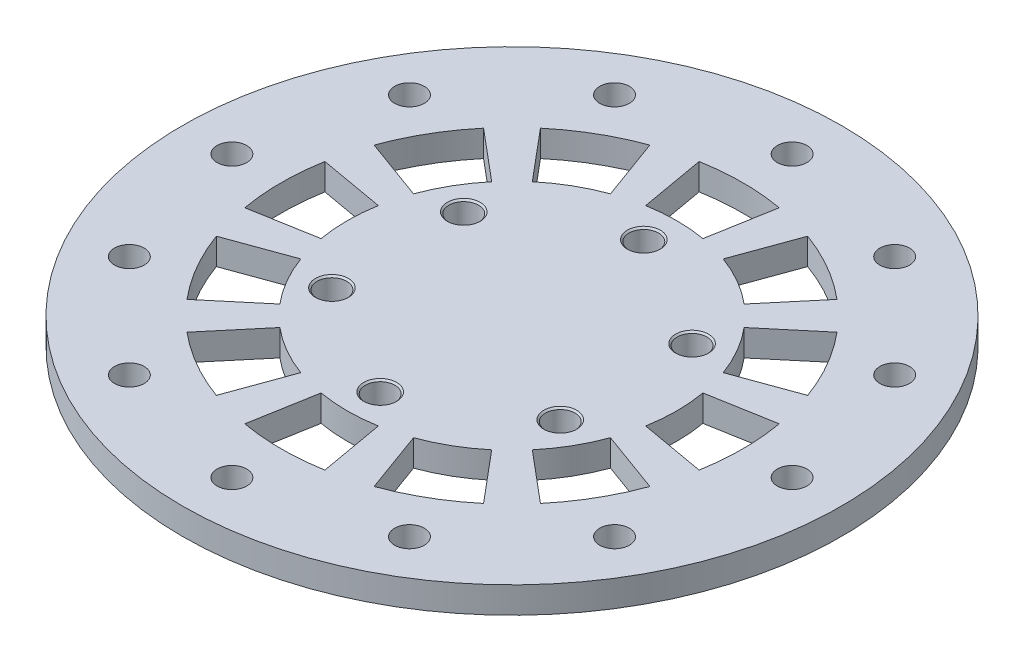
SolidWorks part; units mm, degrees
ref_plane "Спереди" through (0, 0, 0) normal (0, 0, 1) x (1, 0, 0)
ref_plane "Сверху" through (0, 0, 0) normal (0, 1, 0) x (1, 0, 0)
ref_plane "Справа" through (0, 0, 0) normal (1, 0, 0) x (0, 0, -1)
other "Configuration Table"
sketch "Эскиз1" plane through (0, 0, 0) normal (0, 1, 0) x (1, 0, 0)
  circle A0 centre (0, 0) radius 50
  dimension "D1" = 100
extrude "Бобышка-Вытянуть1" add sketch "Эскиз1" along normal blind 4
sketch "Эскиз2" plane through (0, 0, 0) normal (0, 1, 0) x (1, 0, 0)
  line L2 (8.5505, -23.4923) -> (11.9707, -32.8892)
  line L3 (22.4976, -26.8116) -> (16.0697, -19.1511)
  line L4 (8.5505, -23.4923) -> (11.9707, -32.8892)
  line L5 (22.4976, -26.8116) -> (16.0697, -19.1511)
  line L6 (-4.3412, -24.6202) -> (-6.0777, -34.4683)
  line L7 (6.0777, -34.4683) -> (4.3412, -24.6202)
  line L8 (-4.3412, -24.6202) -> (-6.0777, -34.4683)
  line L9 (6.0777, -34.4683) -> (4.3412, -24.6202)
  line L10 (23.4923, 8.5505) -> (32.8892, 11.9707)
  line L11 (26.8116, 22.4976) -> (19.1511, 16.0697)
  line L12 (23.4923, 8.5505) -> (32.8892, 11.9707)
  line L13 (26.8116, 22.4976) -> (19.1511, 16.0697)
  line L14 (24.6202, -4.3412) -> (34.4683, -6.0777)
  line L15 (34.4683, 6.0777) -> (24.6202, 4.3412)
  line L16 (24.6202, -4.3412) -> (34.4683, -6.0777)
  line L17 (34.4683, 6.0777) -> (24.6202, 4.3412)
  line L18 (19.1511, -16.0697) -> (26.8116, -22.4976)
  line L19 (32.8892, -11.9707) -> (23.4923, -8.5505)
  line L20 (19.1511, -16.0697) -> (26.8116, -22.4976)
  line L21 (32.8892, -11.9707) -> (23.4923, -8.5505)
  line L22 (-8.5505, 23.4923) -> (-11.9707, 32.8892)
  line L23 (-22.4976, 26.8116) -> (-16.0697, 19.1511)
  line L24 (-8.5505, 23.4923) -> (-11.9707, 32.8892)
  line L25 (-22.4976, 26.8116) -> (-16.0697, 19.1511)
  line L26 (4.3412, 24.6202) -> (6.0777, 34.4683)
  line L27 (-6.0777, 34.4683) -> (-4.3412, 24.6202)
  line L28 (4.3412, 24.6202) -> (6.0777, 34.4683)
  line L29 (-6.0777, 34.4683) -> (-4.3412, 24.6202)
  line L30 (16.0697, 19.1511) -> (22.4976, 26.8116)
  line L31 (11.9707, 32.8892) -> (8.5505, 23.4923)
  line L32 (16.0697, 19.1511) -> (22.4976, 26.8116)
  line L33 (11.9707, 32.8892) -> (8.5505, 23.4923)
  line L34 (-16.0697, -19.1511) -> (-22.4976, -26.8116)
  line L35 (-11.9707, -32.8892) -> (-8.5505, -23.4923)
  line L36 (-16.0697, -19.1511) -> (-22.4976, -26.8116)
  line L37 (-11.9707, -32.8892) -> (-8.5505, -23.4923)
  line L38 (-23.4923, -8.5505) -> (-32.8892, -11.9707)
  line L39 (-26.8116, -22.4976) -> (-19.1511, -16.0697)
  line L40 (-23.4923, -8.5505) -> (-32.8892, -11.9707)
  line L41 (-26.8116, -22.4976) -> (-19.1511, -16.0697)
  line L42 (-24.6202, 4.3412) -> (-34.4683, 6.0777)
  line L43 (-34.4683, -6.0777) -> (-24.6202, -4.3412)
  line L44 (-24.6202, 4.3412) -> (-34.4683, 6.0777)
  line L45 (-34.4683, -6.0777) -> (-24.6202, -4.3412)
  line L46 (-19.1511, 16.0697) -> (-26.8116, 22.4976)
  line L47 (-32.8892, 11.9707) -> (-23.4923, 8.5505)
  line L48 (-19.1511, 16.0697) -> (-26.8116, 22.4976)
  line L49 (-32.8892, 11.9707) -> (-23.4923, 8.5505)
  arc A2 (8.5505, -23.4923) -> (16.0697, -19.1511) centre (0, 0) ccw
  arc A3 (11.9707, -32.8892) -> (22.4976, -26.8116) centre (0, 0) ccw
  arc A4 (8.5505, -23.4923) -> (16.0697, -19.1511) centre (0, 0) ccw
  arc A5 (11.9707, -32.8892) -> (22.4976, -26.8116) centre (0, 0) ccw
  arc A6 (-4.3412, -24.6202) -> (4.3412, -24.6202) centre (0, 0) ccw
  arc A7 (-6.0777, -34.4683) -> (6.0777, -34.4683) centre (0, 0) ccw
  arc A8 (-4.3412, -24.6202) -> (4.3412, -24.6202) centre (0, 0) ccw
  arc A9 (-6.0777, -34.4683) -> (6.0777, -34.4683) centre (0, 0) ccw
  arc A10 (23.4923, 8.5505) -> (19.1511, 16.0697) centre (0, 0) ccw
  arc A11 (32.8892, 11.9707) -> (26.8116, 22.4976) centre (0, 0) ccw
  arc A12 (23.4923, 8.5505) -> (19.1511, 16.0697) centre (0, 0) ccw
  arc A13 (32.8892, 11.9707) -> (26.8116, 22.4976) centre (0, 0) ccw
  arc A14 (24.6202, -4.3412) -> (24.6202, 4.3412) centre (0, 0) ccw
  arc A15 (34.4683, -6.0777) -> (34.4683, 6.0777) centre (0, 0) ccw
  arc A16 (24.6202, -4.3412) -> (24.6202, 4.3412) centre (0, 0) ccw
  arc A17 (34.4683, -6.0777) -> (34.4683, 6.0777) centre (0, 0) ccw
  arc A18 (19.1511, -16.0697) -> (23.4923, -8.5505) centre (0, 0) ccw
  arc A19 (26.8116, -22.4976) -> (32.8892, -11.9707) centre (0, 0) ccw
  arc A20 (19.1511, -16.0697) -> (23.4923, -8.5505) centre (0, 0) ccw
  arc A21 (26.8116, -22.4976) -> (32.8892, -11.9707) centre (0, 0) ccw
  arc A22 (-8.5505, 23.4923) -> (-16.0697, 19.1511) centre (0, 0) ccw
  arc A23 (-11.9707, 32.8892) -> (-22.4976, 26.8116) centre (0, 0) ccw
  arc A24 (-8.5505, 23.4923) -> (-16.0697, 19.1511) centre (0, 0) ccw
  arc A25 (-11.9707, 32.8892) -> (-22.4976, 26.8116) centre (0, 0) ccw
  arc A26 (4.3412, 24.6202) -> (-4.3412, 24.6202) centre (0, 0) ccw
  arc A27 (6.0777, 34.4683) -> (-6.0777, 34.4683) centre (0, 0) ccw
  arc A28 (4.3412, 24.6202) -> (-4.3412, 24.6202) centre (0, 0) ccw
  arc A29 (6.0777, 34.4683) -> (-6.0777, 34.4683) centre (0, 0) ccw
  arc A30 (22.4976, 26.8116) -> (11.9707, 32.8892) centre (0, 0) ccw
  arc A31 (16.0697, 19.1511) -> (8.5505, 23.4923) centre (0, 0) ccw
  arc A32 (22.4976, 26.8116) -> (11.9707, 32.8892) centre (0, 0) ccw
  arc A33 (16.0697, 19.1511) -> (8.5505, 23.4923) centre (0, 0) ccw
  arc A34 (-16.0697, -19.1511) -> (-8.5505, -23.4923) centre (0, 0) ccw
  arc A35 (-22.4976, -26.8116) -> (-11.9707, -32.8892) centre (0, 0) ccw
  arc A36 (-16.0697, -19.1511) -> (-8.5505, -23.4923) centre (0, 0) ccw
  arc A37 (-22.4976, -26.8116) -> (-11.9707, -32.8892) centre (0, 0) ccw
  arc A38 (-23.4923, -8.5505) -> (-19.1511, -16.0697) centre (0, 0) ccw
  arc A39 (-32.8892, -11.9707) -> (-26.8116, -22.4976) centre (0, 0) ccw
  arc A40 (-23.4923, -8.5505) -> (-19.1511, -16.0697) centre (0, 0) ccw
  arc A41 (-32.8892, -11.9707) -> (-26.8116, -22.4976) centre (0, 0) ccw
  arc A42 (-24.6202, 4.3412) -> (-24.6202, -4.3412) centre (0, 0) ccw
  arc A43 (-34.4683, 6.0777) -> (-34.4683, -6.0777) centre (0, 0) ccw
  arc A44 (-24.6202, 4.3412) -> (-24.6202, -4.3412) centre (0, 0) ccw
  arc A45 (-34.4683, 6.0777) -> (-34.4683, -6.0777) centre (0, 0) ccw
  arc A46 (-26.8116, 22.4976) -> (-32.8892, 11.9707) centre (0, 0) ccw
  arc A47 (-19.1511, 16.0697) -> (-23.4923, 8.5505) centre (0, 0) ccw
  arc A48 (-26.8116, 22.4976) -> (-32.8892, 11.9707) centre (0, 0) ccw
  arc A49 (-19.1511, 16.0697) -> (-23.4923, 8.5505) centre (0, 0) ccw
  dimension "D1" = 0
  dimension "D2" = 0
  dimension "D3" = 0
  dimension "D4" = 0
  dimension "D5" = 0
  dimension "D6" = 0
  dimension "D7" = 0
  dimension "D8" = 0
  dimension "D9" = 0
  dimension "D10" = 0
  dimension "D11" = 0
  dimension "D12" = 0
extrude "Вырез-Вытянуть2" cut sketch "Эскиз2" along normal through all
hole_wizard "Отверстие с зазором M41" positions "Эскиз3" profile "Эскиз4" hole size "M4" standard "DIN" end condition through all
sketch "Эскиз3" plane through (0, 0, 0) normal (0, -1, 0) x (-1, 0, 0)
  circle A0 centre (0, 0) radius 42.5 construction
  point P0 (0, 42.5)
  point P13 (21.25, 36.8061)
  point P14 (36.8061, 21.25)
  point P15 (42.5, 0)
  point P16 (36.8061, -21.25)
  point P17 (21.25, -36.8061)
  point P18 (0, -42.5)
  point P19 (-21.25, -36.8061)
  point P20 (-36.8061, -21.25)
  point P21 (-42.5, 0)
  point P22 (-36.8061, 21.25)
  point P23 (-21.25, 36.8061)
  dimension "D1" = 85
  dimension "D2" = 12
sketch "Эскиз4" plane through (0, 0, -42.5) normal (1, 0, 0) x (0, 0, -1)
  line L0 (0, 0) -> (0, 4)
  line L1 (0, 4) -> (2.25, 4)
  line L2 (2.25, 4) -> (2.25, 0.25)
  line L3 (2.25, 0.25) -> (2.5, 0)
  line L5 (2.5, 0) -> (0, 0)
  line L6 (-2.25, 0.25) -> (-2.5, 0) construction
  line L11 (0, -6.35) -> (0, 107.95) construction
  dimension "Диаметр сквозного отверстия" = 4.5
  dimension "Глубина сквозного отверстия" = 4
  dimension "Диаметр передней зенковки" = 5
  dimension "Угол передней зенковки" = 90
hole_wizard "Отверстие с зазором M42" positions "Эскиз5" profile "Эскиз6" hole size "M4" standard "DIN" end condition through all
sketch "Эскиз5" plane through (0, 4, 0) normal (0, 1, 0) x (1, 0, 0)
  circle A0 centre (0, 0) radius 20 construction
  point P5 (0, 20)
  point P14 (17.3205, 10)
  point P15 (17.3205, -10)
  point P16 (0, -20)
  point P17 (-17.3205, -10)
  point P18 (-17.3205, 10)
  dimension "D1" = 40
  dimension "D2" = 6
sketch "Эскиз6" plane through (-17.3205, 4, -10) normal (1, 0, 0) x (0, 0, 1)
  line L0 (0, 0) -> (0, 4)
  line L1 (0, 4) -> (2.25, 4)
  line L2 (2.25, 4) -> (2.25, 0.25)
  line L3 (2.25, 0.25) -> (2.5, 0)
  line L5 (2.5, 0) -> (0, 0)
  line L6 (-2.25, 0.25) -> (-2.5, 0) construction
  line L11 (0, -6.35) -> (0, 107.95) construction
  dimension "Диаметр сквозного отверстия" = 4.5
  dimension "Глубина сквозного отверстия" = 4
  dimension "Диаметр передней зенковки" = 5
  dimension "Угол передней зенковки" = 90
